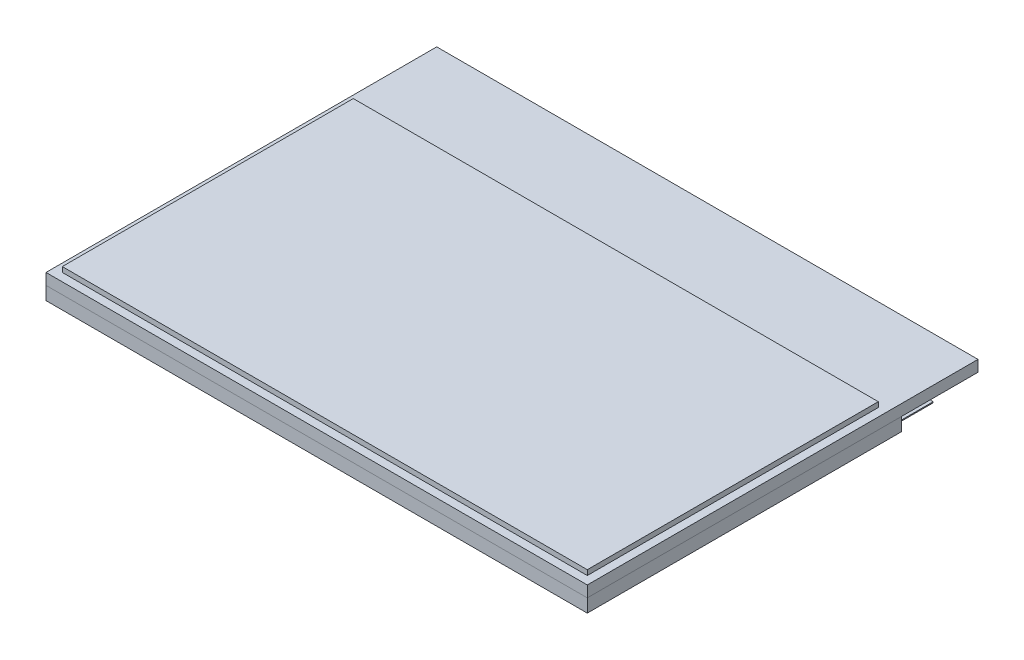
SolidWorks part; units mm, degrees
ref_plane "Front Plane" through (0, 0, 0) normal (0, 0, 1) x (1, 0, 0)
ref_plane "Top Plane" through (0, 0, 0) normal (0, 1, 0) x (1, 0, 0)
ref_plane "Right Plane" through (0, 0, 0) normal (1, 0, 0) x (0, 0, -1)
sketch "Sketch1" plane through (0, 0, 0) normal (0, 1, 0) x (1, 0, 0)
  line L1 (-13.3, -9.6) -> (13.3, -9.6)
  line L2 (-13.3, -9.6) -> (-13.3, 9.6)
  line L3 (-13.3, 9.6) -> (13.3, 9.6)
  line L4 (13.3, -9.6) -> (13.3, 9.6)
  line L5 (-13.3, -9.6) -> (13.3, 9.6) construction
  line L6 (-13.3, 9.6) -> (13.3, -9.6) construction
  point P0 (0, 0)
  dimension "D1" = 26.6
  dimension "D2" = 19.2
extrude "Boss-Extrude1" add sketch "Sketch1" along normal blind 0.55
sketch "Sketch2" plane through (0, 0.55, 0) normal (0, 1, 0) x (1, 0, 0)
  line L0 (-13.3, 9.6) -> (-13.3, -9.6) construction
  line L1 (-12.9, 5.1) -> (12.9, 5.1)
  line L2 (-12.9, 5.1) -> (-12.9, -9.2)
  line L3 (-12.9, -9.2) -> (12.9, -9.2)
  line L4 (12.9, 5.1) -> (12.9, -9.2)
  line L5 (13.3, -9.6) -> (13.3, 9.6) construction
  line L6 (-13.3, -9.6) -> (13.3, -9.6) construction
  dimension "D1" = 0.4
  dimension "D2" = 0.4
  dimension "D3" = 0.4
  dimension "D4" = 14.3
sketch "Sketch3" plane through (0, 0, 0) normal (0, -1, 0) x (1, 0, 0)
  line L0 (-13.3, -9.6) -> (-13.3, 9.6) construction
  line L1 (13.3, 9.6) -> (-13.3, 9.6)
  line L2 (13.3, 9.6) -> (13.3, -5.85)
  line L3 (13.3, -5.85) -> (-13.3, -5.85)
  line L4 (-13.3, 9.6) -> (-13.3, -5.85)
  dimension "D1" = 15.45
extrude "Boss-Extrude2" add sketch "Sketch3" along direction (0, -1, 0) on the side of the normal blind 0.65 separate body
sketch "Sketch4" plane through (0, -0.65, 0) normal (0, -1, 0) x (1, 0, 0)
  line L0 (-13.3, 9.6) -> (-13.3, -5.85) construction
  line L1 (-12.8, 9.1) -> (12.8, 9.1)
  line L2 (-12.8, 9.1) -> (-12.8, -7.9)
  line L3 (-12.8, -7.9) -> (12.8, -7.9)
  line L4 (12.8, 9.1) -> (12.8, -7.9)
  line L5 (13.3, 9.6) -> (-13.3, 9.6) construction
  line L6 (13.3, -5.85) -> (13.3, 9.6) construction
  dimension "D1" = 0.5
  dimension "D2" = 0.5
  dimension "D3" = 0.5
  dimension "D4" = 17
extrude "Boss-Extrude3" add sketch "Sketch4" along normal blind 0.05 separate body
extrude "Boss-Extrude4" add sketch "Sketch2" along normal blind 0.25 separate body
equation "\"D2@Sketch2\"=\"D1@Sketch2\""
equation "\"D3@Sketch2\"=\"D1@Sketch2\""
equation "\"D2@Sketch4\"=\"D1@Sketch4\""
equation "\"D3@Sketch4\"=\"D1@Sketch4\""
